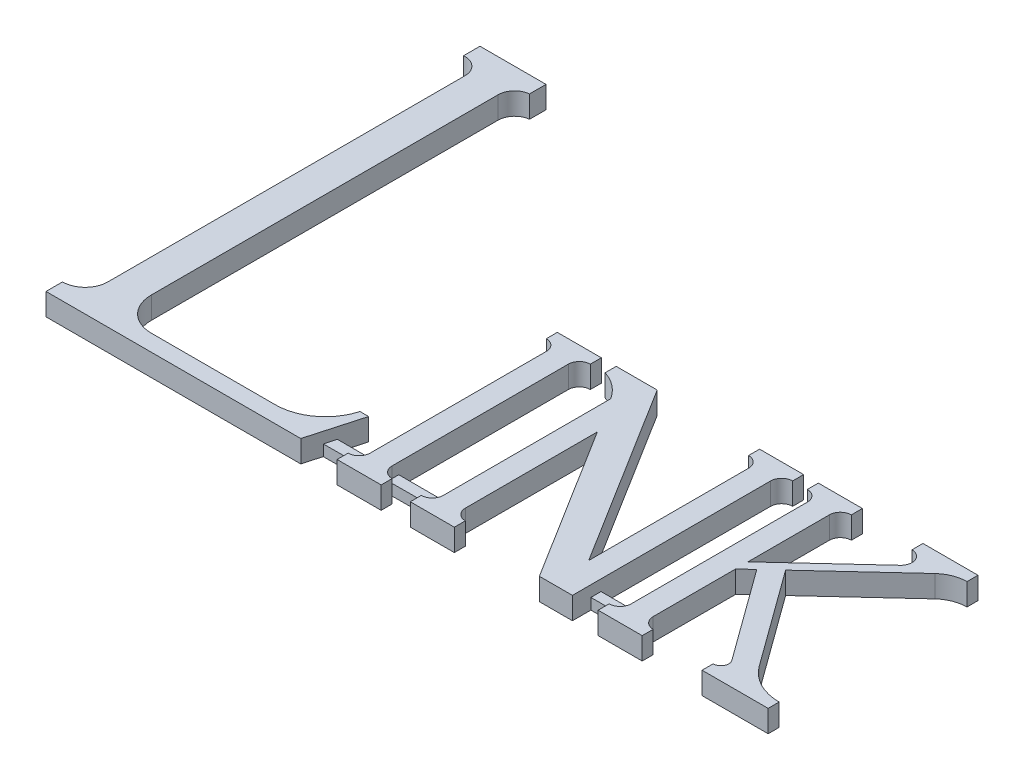
SolidWorks part; units mm, degrees
ref_plane "Front Plane" through (0, 0, 0) normal (0, 0, 1) x (1, 0, 0)
ref_plane "Top Plane" through (0, 0, 0) normal (0, 1, 0) x (1, 0, 0)
ref_plane "Right Plane" through (0, 0, 0) normal (1, 0, 0) x (0, 0, -1)
sketch "Sketch2" plane through (0, 0, 0) normal (0, 1, 0) x (1, 0, 0)
  line L0 (0, 16.2602) -> (0, 222.25)
  line L1 (-10.418, 231.733) -> (-10.418, 241.258)
  line L2 (-10.418, 241.258) -> (27.682, 241.258)
  line L3 (27.682, 241.258) -> (27.682, 231.733)
  line L4 (0, -6.35) -> (127, -6.35)
  line L8 (19.05, 222.25) -> (19.05, 22.225)
  line L9 (38.1, 3.175) -> (109.6599, 3.175)
  line L10 (154.7924, 0.0039) -> (154.7924, -6.3461)
  line L11 (154.7924, -6.3461) -> (180.1924, -6.3461)
  line L12 (180.1924, -6.3461) -> (180.1924, 0.0039)
  line L13 (154.7924, -6.3461) -> (154.7924, 11.4358) construction
  line L14 (161.1385, 6.3539) -> (173.8385, 6.3539) construction
  line L15 (180.1924, -6.3461) -> (180.1924, 11.4358) construction
  line L16 (161.1385, 6.3539) -> (161.1385, 107.9539)
  line L17 (173.8385, 6.3539) -> (173.8385, 107.9539)
  line L18 (180.1846, 114.3039) -> (180.1846, 120.6539)
  line L20 (154.7846, 120.6539) -> (154.7846, 114.3039)
  line L21 (180.1846, 120.6539) -> (180.1846, 102.872) construction
  line L22 (154.7846, 120.6539) -> (154.7846, 102.872) construction
  line L26 (222.4032, -6.3461) -> (222.4032, 11.4358) construction
  line L27 (197.0032, -6.3461) -> (197.0032, 11.4358) construction
  line L28 (197.0032, 0.0039) -> (197.0032, -6.3461)
  line L29 (197.0032, -6.3461) -> (222.4032, -6.3461)
  line L30 (222.4032, -6.3461) -> (222.4027, 0.0039)
  line L33 (271.4505, -6.3461) -> (290.5044, -6.3461)
  line L34 (290.5044, -6.3461) -> (290.5044, 107.9539)
  line L41 (154.7846, 120.6539) -> (180.1846, 120.6539)
  line L42 (271.4505, 120.6539) -> (271.4505, 102.872) construction
  line L43 (296.8505, 120.6539) -> (296.8505, 102.872) construction
  line L44 (271.4505, 120.6539) -> (271.4505, 114.3039)
  line L45 (296.8505, 114.3039) -> (296.8505, 120.6539)
  line L46 (296.8505, 120.6539) -> (271.4505, 120.6539)
  line L50 (203.3522, 6.3539) -> (203.3522, 102.872)
  line L51 (216.0522, 82.5034) -> (271.4505, -6.3461)
  line L52 (216.0522, 6.3539) -> (216.0522, 82.5034)
  line L53 (277.8044, 107.9539) -> (277.8044, 15.7456)
  line L54 (277.8044, 15.7456) -> (212.3933, 120.6539)
  line L55 (212.3933, 120.6539) -> (188.7492, 120.6539)
  line L56 (188.7492, 120.6539) -> (188.7492, 114.3039)
  line L57 (305.3328, -6.3461) -> (305.3328, 11.4358) construction
  line L58 (330.7328, -6.3461) -> (330.7323, 0.0039)
  line L59 (305.3328, -6.3461) -> (330.7328, -6.3461)
  line L60 (330.7328, -6.3461) -> (330.7328, 11.4358) construction
  line L61 (305.3328, 0.0039) -> (305.3328, -6.3461)
  line L62 (330.7308, 120.6539) -> (330.7308, 102.872) construction
  line L63 (305.3308, 120.6539) -> (305.3313, 114.3039)
  line L64 (330.7308, 120.6539) -> (305.3308, 120.6539)
  line L65 (305.3308, 120.6539) -> (305.3308, 102.872) construction
  line L66 (330.7308, 114.3039) -> (330.7308, 120.6539)
  line L67 (311.6818, 6.3539) -> (311.6818, 107.9539)
  line L68 (324.3818, 6.3539) -> (324.3818, 53.8887)
  line L69 (324.3818, 61.0082) -> (370.0114, 103.1757)
  line L70 (324.3818, 107.9539) -> (324.3818, 61.0082)
  line L71 (324.3818, 53.8887) -> (330.7308, 59.756)
  line L72 (365.6568, 120.6539) -> (365.6568, 114.3039)
  line L73 (397.4068, 120.6539) -> (365.6568, 120.6539)
  line L74 (397.4068, 114.3039) -> (397.4068, 120.6539)
  line L75 (397.4068, 114.3039) -> (403.7575, 114.3039) construction
  line L76 (365.6568, 114.3039) -> (366.1573, 114.3039) construction
  line L77 (330.7308, 59.756) -> (368.9334, 7.1747)
  line L78 (339.3677, 67.7376) -> (379.8797, 11.9777)
  line L79 (365.2797, -6.3461) -> (403.3797, -6.3461)
  line L80 (365.2797, 0.0039) -> (365.2797, -6.3461)
  line L81 (403.3797, -6.3461) -> (403.3797, 0.0039)
  line L82 (365.2797, 0.0039) -> (345.048, 0.0039) construction
  line L83 (403.3797, 0.0039) -> (413.1692, 0.0039)
  line L84 (339.3677, 67.7376) -> (384.1391, 109.1121)
  line L85 (127, -6.35) -> (133.8355, -6.35)
  line L86 (133.8355, -6.35) -> (142.4102, 24.2202)
  line L87 (142.4102, 24.2202) -> (137.4204, 24.2202)
  line L88 (137.4204, 24.2202) -> (140.816, 36.3259) construction
  line L89 (0, -6.35) -> (-13.0852, -6.35)
  line L90 (-13.0852, -6.35) -> (-13.0852, 3.175)
  line L91 (-13.0852, 3.175) -> (-32.2057, 3.175) construction
  arc A1 (-10.418, 231.733) -> (0, 222.25) centre (-9.525, 222.25) cw
  arc A2 (19.05, 222.25) -> (27.682, 231.733) centre (28.575, 222.25) cw
  arc A6 (173.8385, 6.3539) -> (180.1924, 0.0039) centre (180.1885, 6.3539) ccw
  arc A7 (161.1385, 6.3539) -> (154.7924, 0.0039) centre (154.7885, 6.3539) cw
  arc A8 (161.1385, 107.9539) -> (154.7846, 114.3039) centre (154.7885, 107.9539) ccw
  arc A9 (173.8385, 107.9539) -> (180.1846, 114.3039) centre (180.1885, 107.9539) cw
  arc A11 (216.0522, 6.3539) -> (222.4027, 0.0039) centre (222.4022, 6.3539) ccw
  arc A12 (203.3522, 6.3539) -> (197.0032, 0.0039) centre (197.0022, 6.3539) cw
  arc A15 (203.3522, 102.872) -> (188.7492, 114.3039) centre (180.347, 88.5281) ccw
  arc A16 (311.6818, 6.3539) -> (305.3328, 0.0039) centre (305.3318, 6.3539) cw
  arc A17 (277.8044, 107.9539) -> (271.4505, 114.3039) centre (271.4544, 107.9539) ccw
  arc A18 (290.5044, 107.9539) -> (296.8505, 114.3039) centre (296.8544, 107.9539) cw
  arc A19 (324.3818, 6.3539) -> (330.7323, 0.0039) centre (330.7318, 6.3539) ccw
  arc A20 (324.3818, 107.9539) -> (330.7308, 114.3039) centre (330.7318, 107.9539) cw
  arc A21 (311.6818, 107.9539) -> (305.3313, 114.3039) centre (305.3318, 107.9539) ccw
  arc A22 (384.1391, 109.1121) -> (397.4068, 114.3039) centre (397.4068, 94.7551) cw
  arc A23 (365.6568, 114.3039) -> (370.0114, 103.1757) centre (365.6568, 107.8878) cw
  arc A24 (365.2797, 0.0039) -> (368.9334, 7.1747) centre (365.2797, 4.5201) ccw
  arc A25 (379.8797, 11.9777) -> (403.3797, 0.0039) centre (403.3797, 29.0515) ccw
  arc A26 (109.6599, 3.175) -> (137.4204, 24.2202) centre (109.6599, 32.0068) ccw
  arc A27 (-13.0852, 3.175) -> (0, 16.2602) centre (-13.0852, 16.2602) ccw
  arc A28 (19.05, 22.225) -> (38.1, 3.175) centre (38.1, 22.225) ccw
  point P115 (0, 0)
  dimension "D1" = 9.525
  dimension "D7" = 9.525
  dimension "D8" = 31.75
  dimension "D9" = 9.525
  dimension "D10" = 19.05
  dimension "D14" = 6.35
  dimension "D15" = 6.35
  dimension "D19" = 25.4
  dimension "D21" = 25.4
  dimension "D24" = 25.4
  dimension "D26" = 6.35
  dimension "D28" = 31.75
  dimension "D20" = 6.35
  dimension "D31" = 5.2287
  dimension "D2" = 228.6
  dimension "D3" = 127
  dimension "D4" = 9.525
  dimension "D5" = 19.05
  dimension "D6" = 9.525
  dimension "D11" = 36
  dimension "D13" = 38.1
  dimension "D16" = 25.4
  dimension "D18" = 101.6
  dimension "D22" = 25.4
  dimension "D23" = 6.35
  dimension "D25" = 25.4
  dimension "D27" = 6.35
  dimension "D29" = 6.35
  dimension "D30" = 132.742
  dimension "D32" = 59.6457
  dimension "D34" = 101.6
  dimension "D35" = 38.1
  dimension "D36" = 6.35
  dimension "D37" = 11.6789
  dimension "D38" = 6.349
extrude "Boss-Extrude1" add sketch "Sketch2" along normal blind 12.7 contours L17 A9 L18 L41 L20 A8 L16 A7 L10 L11 L12 A6 | L34 A18 L45 L46 L44 A17 L53 L54 L55 L56 A15 L50 A12 L28 L29 L30 A11 L52 L51 L33 | A25 L78 L84 A22 L74 L73 L72 A23 L69 L70 A20 L66 L64 L63 A21 L67 A16 L61 L59 L58 A19 L68 L71 L77 A24 L80 L79 L81 | L4 L85 L86 L87 A26 L9 A28 L8 A2 L3 L2 L1 A1 L0 A27 L90 L89
sketch "Sketch4" plane through (0, 0, 0) normal (0, 1, 0) x (1, 0, 0)
  line L0 (136.6816, 3.7968) -> (376.3888, 4.5553)
  line L1 (133.8355, -6.35) -> (142.4102, 24.2202) construction
  line L2 (376.3888, 4.5553) -> (376.3888, 10.1468)
  line L3 (376.3888, 10.1468) -> (136.6816, 10.1468)
  line L4 (136.6816, 10.1468) -> (136.6816, 3.7968)
  dimension "D1" = 6.35
extrude "Boss-Extrude2" add sketch "Sketch4" along normal blind 6.35 contours L3 L4 L0 L2
ref_plane "Plane1" through (216.0522, 6.35, -10.1468) normal (-1, 0, 0) x (0, 0, 1)
sketch "Sketch6" plane through (0, 12.7, 0) normal (0, 1, 0) x (1, 0, 0)
  line L0 (324.6926, 4.3917) -> (369.7959, 4.5344) construction
  line L1 (368.9334, 7.1747) -> (366.774, 10.1468) construction
  line L2 (366.774, 10.1468) -> (324.3818, 10.1468) construction
  line L3 (324.3818, 10.1468) -> (324.3818, 6.3539) construction
  line L4 (216.4852, 4.0493) -> (264.8735, 4.2024) construction
  line L5 (264.8735, 4.2024) -> (261.1671, 10.1468) construction
  line L6 (261.1671, 10.1468) -> (216.0522, 10.1468) construction
  line L7 (216.0522, 10.1468) -> (216.0522, 6.3539) construction
  line L8 (324.6926, 4.3917) -> (369.7959, 4.5344)
  line L9 (368.9334, 7.1747) -> (366.774, 10.1468)
  line L10 (366.774, 10.1468) -> (324.3818, 10.1468)
  line L11 (324.3818, 10.1468) -> (324.3818, 6.3539)
  line L12 (216.4852, 4.0493) -> (264.8735, 4.2024)
  line L13 (264.8735, 4.2024) -> (261.1671, 10.1468)
  line L14 (261.1671, 10.1468) -> (216.0522, 10.1468)
  line L15 (216.0522, 10.1468) -> (216.0522, 6.3539)
  arc A0 (324.3818, 6.3539) -> (324.6926, 4.3917) centre (330.7318, 6.3539) ccw construction
  arc A1 (369.7959, 4.5344) -> (368.9334, 7.1747) centre (365.2797, 4.5201) ccw construction
  arc A2 (216.0522, 6.3539) -> (216.4852, 4.0493) centre (222.4022, 6.3539) ccw construction
  arc A3 (324.3818, 6.3539) -> (324.6926, 4.3917) centre (330.7318, 6.3539) ccw
  arc A4 (369.7959, 4.5344) -> (368.9334, 7.1747) centre (365.2797, 4.5201) ccw
  arc A5 (216.0522, 6.3539) -> (216.4852, 4.0493) centre (222.4022, 6.3539) ccw
extrude "Cut-Extrude2" cut sketch "Sketch6" against normal through all both and the other way through all
